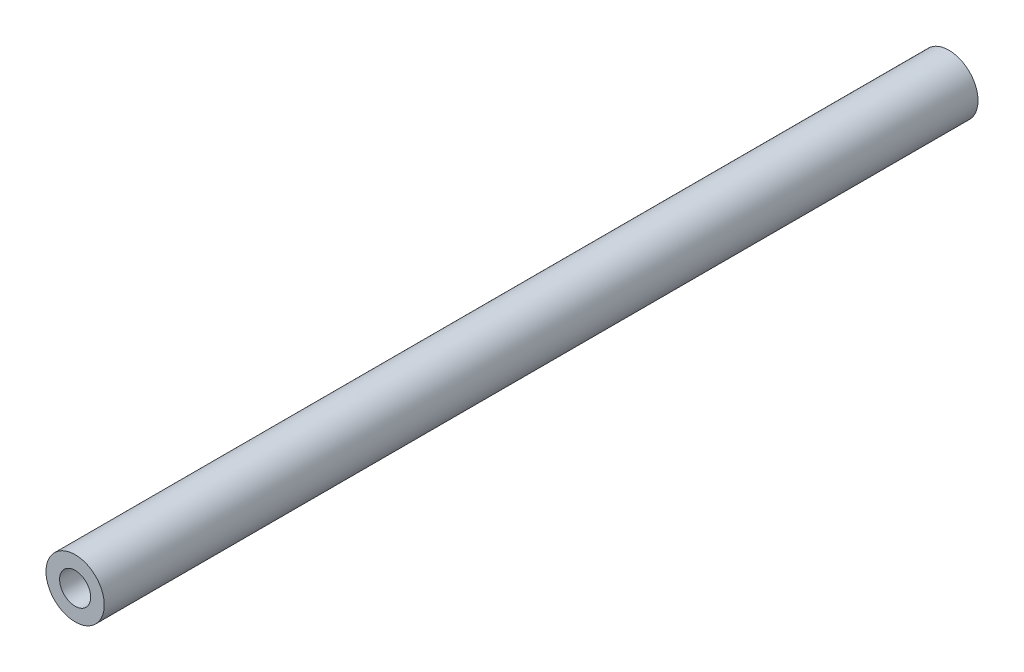
SolidWorks part; units mm, degrees
ref_plane "Ebene vorne" through (0, 0, 0) normal (0, 0, 1) x (1, 0, 0)
ref_plane "Ebene oben" through (0, 0, 0) normal (0, 1, 0) x (1, 0, 0)
ref_plane "Ebene rechts" through (0, 0, 0) normal (1, 0, 0) x (0, 0, -1)
sketch "Skizze1" plane through (0, 0, 0) normal (0, 0, 1) x (1, 0, 0)
  circle A0 centre (0, 0) radius 3
  dimension "D1" = 6
extrude "Aufsatz-Linear austragen1" add sketch "Skizze1" along normal blind 90
sketch "Skizze3" plane through (0, 0, 90) normal (0, 0, 1) x (1, 0, 0)
  circle A0 centre (0, 0) radius 1.6
  dimension "D1" = 3.2
extrude "Schnitt-Linear austragen1" cut sketch "Skizze3" against normal blind 4.5
sketch "Skizze4" plane through (0, 0, 0) normal (0, 0, -1) x (-1, 0, 0)
  circle A0 centre (0, 0) radius 1.6
  dimension "D1" = 3.2
extrude "Schnitt-Linear austragen2" cut sketch "Skizze4" against normal blind 4.5
